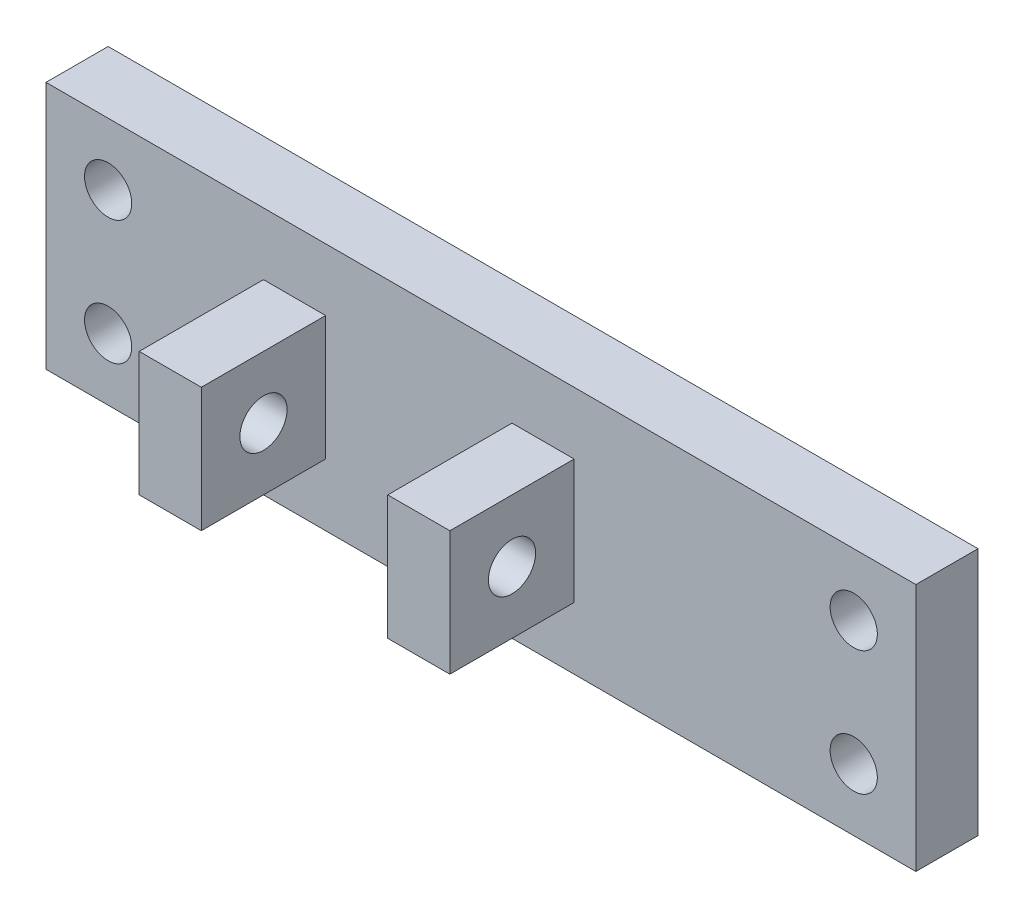
SolidWorks part; units mm, degrees
ref_plane "正面" through (0, 0, 0) normal (0, 0, 1) x (1, 0, 0)
ref_plane "平面" through (0, 0, 0) normal (0, 1, 0) x (1, 0, 0)
ref_plane "右側面" through (0, 0, 0) normal (1, 0, 0) x (0, 0, -1)
sketch "ｽｹｯﾁ1" plane through (0, 0, 0) normal (0, 0, 1) x (1, 0, 0)
  line L1 (35, -10) -> (-35, -10)
  line L2 (35, -10) -> (35, 10)
  line L3 (35, 10) -> (-35, 10)
  line L4 (-35, -10) -> (-35, 10)
  line L5 (35, -10) -> (-35, 10) construction
  line L6 (35, 10) -> (-35, -10) construction
  point P0 (0, 0)
  dimension "D1" = 20
  dimension "D2" = 70
extrude "ﾎﾞｽ - 押し出し1" add sketch "ｽｹｯﾁ1" along normal blind 5
sketch "ｽｹｯﾁ2" plane through (0, 0, 5) normal (0, 0, 1) x (1, 0, 0)
  line L1 (30, -5) -> (-30, -5) construction
  line L2 (30, -5) -> (30, 5) construction
  line L3 (30, 5) -> (-30, 5) construction
  line L4 (-30, -5) -> (-30, 5) construction
  line L5 (30, -5) -> (-30, 5) construction
  line L6 (30, 5) -> (-30, -5) construction
  circle A0 centre (-30, 5) radius 1.9
  circle A1 centre (-30, -5) radius 1.9
  circle A2 centre (30, 5) radius 1.9
  circle A3 centre (30, -5) radius 1.9
  point P0 (0, 0)
  dimension "D3" = 3.8
  dimension "D1" = 60
  dimension "D2" = 10
extrude "ｶｯﾄ - 押し出し1" cut sketch "ｽｹｯﾁ2" against normal blind 5
sketch "ｽｹｯﾁ3" plane through (0, 0, 5) normal (0, 0, 1) x (1, 0, 0)
  line L0 (-35, 10) -> (-35, -10) construction
  line L1 (7.5, -5) -> (-17.5, -5)
  line L2 (7.5, -5) -> (7.5, 5)
  line L3 (7.5, 5) -> (-17.5, 5)
  line L4 (-17.5, -5) -> (-17.5, 5)
  line L5 (7.5, -5) -> (-17.5, 5) construction
  line L6 (7.5, 5) -> (-17.5, -5) construction
  circle A1 centre (-30, 5) radius 1.9 construction
  point P0 (-5, 0)
  point P9 (-35, 0)
  dimension "D1" = 25
  dimension "D2" = 25
  dimension "D3" = 10
extrude "ﾎﾞｽ - 押し出し2" add sketch "ｽｹｯﾁ3" along normal blind 10
sketch "ｽｹｯﾁ4" plane through (0, 0, 15) normal (0, 0, 1) x (1, 0, 0)
  line L9 (7.5, 5) -> (-17.5, 5) construction
  line L10 (-12.5, 5) -> (2.5, 5)
  line L11 (-12.5, 5) -> (-12.5, -5)
  line L12 (-12.5, -5) -> (2.5, -5)
  line L13 (2.5, 5) -> (2.5, -5)
  line L14 (-17.5, -5) -> (7.5, -5) construction
  line L15 (-17.5, 5) -> (-17.5, -5) construction
  line L16 (7.5, -5) -> (7.5, 5) construction
  dimension "D1" = 5
  dimension "D2" = 5
extrude "ｶｯﾄ - 押し出し2" cut sketch "ｽｹｯﾁ4" against normal blind 10
sketch "ｽｹｯﾁ5" plane through (-17.5, 0, 0) normal (-1, 0, 0) x (0, 0, 1)
  line L0 (15, 5) -> (15, -5) construction
  circle A0 centre (10, 0) radius 1.9
  point P4 (0, 0)
  point P5 (15, 0)
  dimension "D2" = 3.8
  dimension "D1" = 5
extrude "ｶｯﾄ - 押し出し3" cut sketch "ｽｹｯﾁ5" against normal through all
